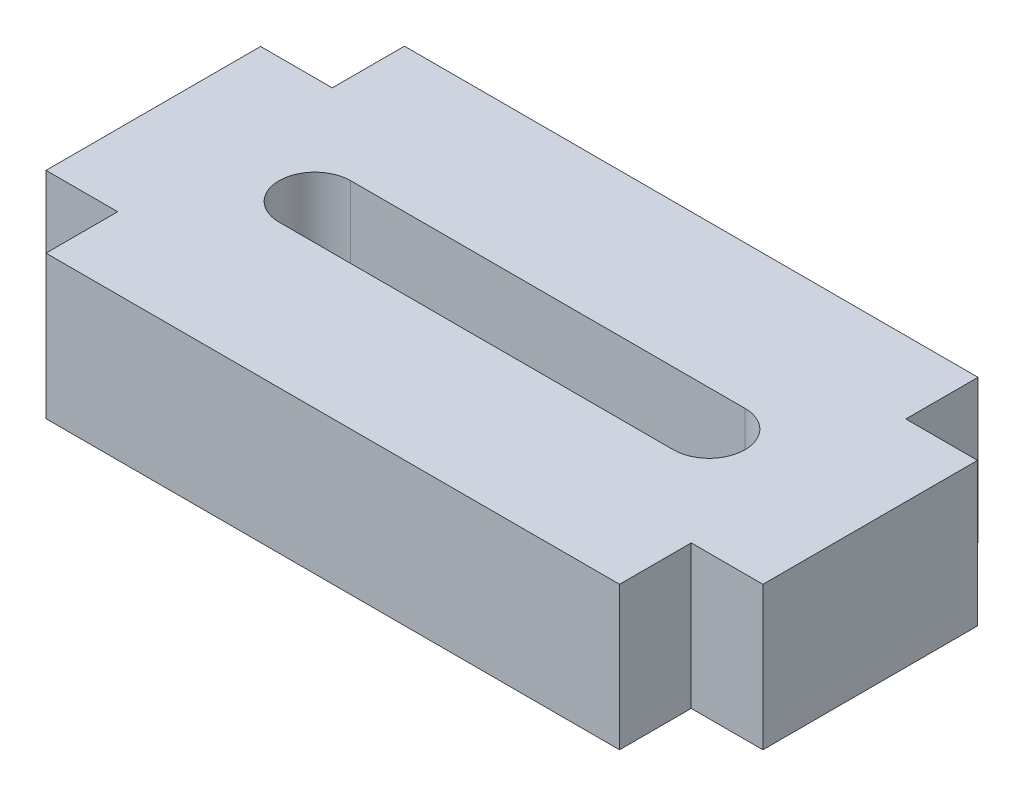
SolidWorks part; units mm, degrees
ref_plane "Front Plane" through (0, 0, 0) normal (0, 0, 1) x (1, 0, 0)
ref_plane "Top Plane" through (0, 0, 0) normal (0, 1, 0) x (1, 0, 0)
ref_plane "Right Plane" through (0, 0, 0) normal (1, 0, 0) x (0, 0, -1)
sketch "Sketch2" plane through (0, 0, 0) normal (0, 1, 0) x (1, 0, 0)
  line L1 (-25, 12.5) -> (25, 12.5)
  line L2 (-25, 12.5) -> (-25, -12.5)
  line L3 (-25, -12.5) -> (25, -12.5)
  line L4 (25, 12.5) -> (25, -12.5)
  line L5 (-25, 12.5) -> (25, -12.5) construction
  line L6 (-25, -12.5) -> (25, 12.5) construction
  point P0 (0, 0)
  dimension "D1" = 50
  dimension "D2" = 25
extrude "Boss-Extrude1" add sketch "Sketch2" along normal blind 10
sketch "Sketch3" plane through (0, 10, 0) normal (0, 1, 0) x (1, 0, 0)
  line L1 (25, 12.5) -> (20, 12.5)
  line L2 (25, 12.5) -> (25, 7.4657)
  line L3 (25, 7.4657) -> (20, 7.4657)
  line L4 (20, 12.5) -> (20, 7.4657)
  line L5 (25, -12.5) -> (20, -12.5)
  line L6 (25, -12.5) -> (25, -7.5)
  line L7 (25, -7.5) -> (20, -7.5)
  line L8 (20, -12.5) -> (20, -7.5)
  dimension "D1" = 5
  dimension "D2" = 5
  dimension "D3" = 5.0343
extrude "Cut-Extrude1" cut sketch "Sketch3" against normal through all
mirror "Mirror1" about plane through (0, 0, 0) normal (1, 0, 0) of "Cut-Extrude1"
sketch "Sketch4" plane through (0, 10, 0) normal (0, 1, 0) x (1, 0, 0)
  line L0 (-13.75, 0) -> (13.75, 0) construction
  line L1 (-13.75, 2.5) -> (13.75, 2.5)
  line L2 (-13.75, -2.5) -> (13.75, -2.5)
  arc A0 (-13.75, 2.5) -> (-13.75, -2.5) centre (-13.75, 0) ccw
  arc A1 (13.75, -2.5) -> (13.75, 2.5) centre (13.75, 0) ccw
  point P2 (0, 0)
  dimension "D1" = 2.5
  dimension "D2" = 27.5
extrude "Cut-Extrude2" cut sketch "Sketch4" against normal through all
